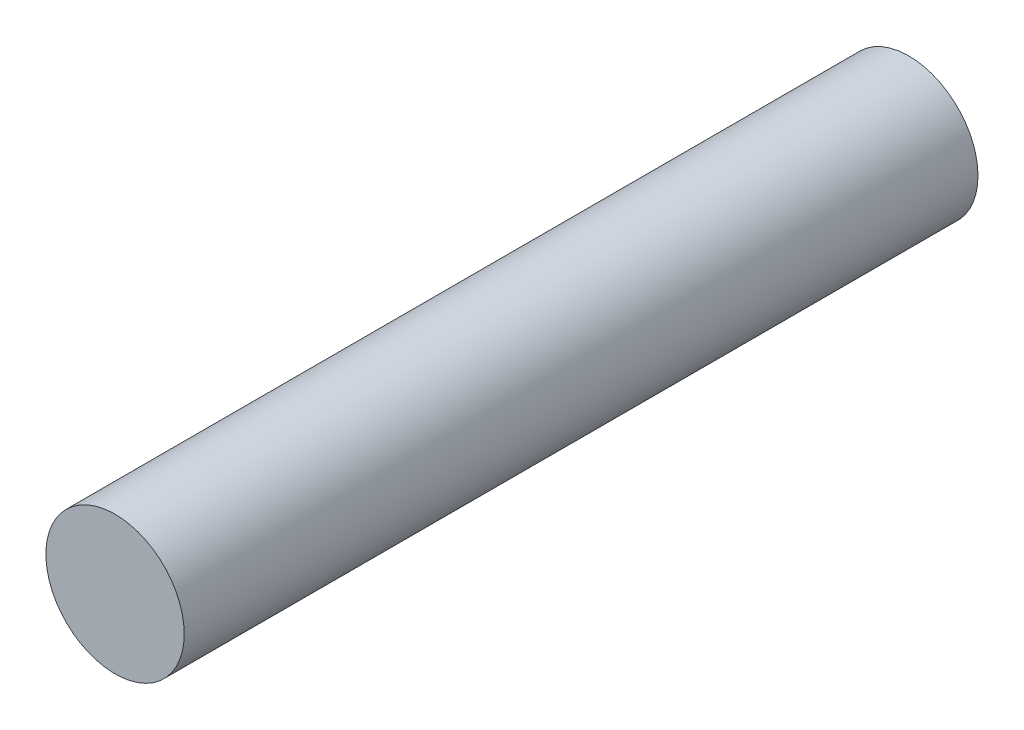
SolidWorks part; units mm, degrees
ref_plane "Front Plane" through (0, 0, 0) normal (0, 0, 1) x (1, 0, 0)
ref_plane "Top Plane" through (0, 0, 0) normal (0, 1, 0) x (1, 0, 0)
ref_plane "Right Plane" through (0, 0, 0) normal (1, 0, 0) x (0, 0, -1)
sketch "Sketch1" plane through (0, 0, 0) normal (0, 0, 1) x (1, 0, 0)
  circle A0 centre (0, 0) radius 1.2
  dimension "D1" = 2.4
extrude "Boss-Extrude1" add sketch "Sketch1" along normal blind 13.77
scale "缩放比例1" scale about centroid uniform scaling yes scale factor 2
